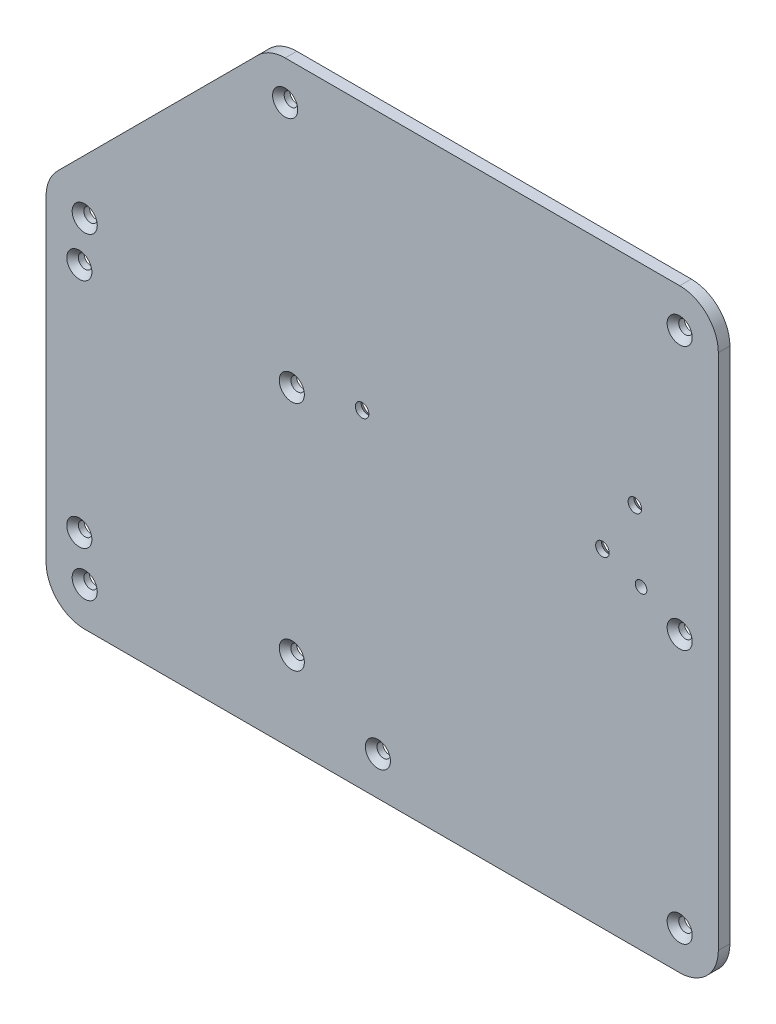
SolidWorks part; units mm, degrees
ref_plane "Piano frontale" through (0, 0, 0) normal (0, 0, 1) x (1, 0, 0)
ref_plane "Piano superiore" through (0, 0, 0) normal (0, 1, 0) x (1, 0, 0)
ref_plane "Piano destro" through (0, 0, 0) normal (1, 0, 0) x (0, 0, -1)
sketch "Schizzo1" plane through (0, 0, 0) normal (0, 0, 1) x (1, 0, 0)
  line L5 (0, 0) -> (170, 0) construction
  line L6 (170, 0) -> (170, 150) construction
  line L7 (170, 150) -> (56.5685, 150) construction
  line L8 (56.5685, 150) -> (0, 93.4315) construction
  line L9 (0, 93.4315) -> (0, 0) construction
  line L10 (172, 152) -> (55.7401, 152)
  line L11 (55.7401, 152) -> (-2, 94.2599)
  line L12 (-2, 94.2599) -> (-2, -2)
  line L13 (-2, -2) -> (172, -2)
  line L14 (172, -2) -> (172, 152)
  dimension "D5" = 2
  dimension "D1" = 150
  dimension "D2" = 80
  dimension "D3" = 170
  dimension "D4" = 135
extrude "Estrusione-Estrusione1" add sketch "Schizzo1" along normal blind 3
fillet "Raccordo1" radius 10 5 edges at (172, -2, 1.5) (-2, -2, 1.5) (55.7401, 152, 1.5) (172, 152, 1.5) (-2, 94.2599, 1.5)
sketch "Schizzo2" plane through (0, 0, 3) normal (0, 0, 1) x (1, 0, 0)
  circle A0 centre (162, 142) radius 1.75
  circle A1 centre (59.8823, 142) radius 1.75
  circle A2 centre (8, 90.1177) radius 1.75
  circle A3 centre (8, 8) radius 1.75
  circle A4 centre (162, 8) radius 1.75
  circle A5 centre (162, 73.8294) radius 1.75
  circle A6 centre (83.8818, 8) radius 1.75
  point P20 (0, 0)
  point P21 (0, 0)
  dimension "D1" = 3.5
extrude "Taglio-Estrusione1" cut sketch "Schizzo2" against normal blind 3
chamfer "Smusso1" distance 1.5 angle 45 7 edges at (163.75, 8, 3) (9.75, 8, 3) (9.75, 90.1177, 3) (61.6323, 142, 3) (163.75, 142, 3) (163.75, 73.8294, 3) (85.6318, 8, 3)
sketch "Schizzo3" plane through (0, 0, 0) normal (0, 0, -1) x (-1, 0, 0)
  circle A1 centre (-61.6, 79) radius 1.75
  circle A3 centre (-6.6, 79) radius 1.75
  circle A4 centre (-6.6, 19) radius 1.75
  circle A6 centre (-61.6, 19) radius 1.75
  dimension "D1" = 3.5
sketch "Schizzo4" plane through (0, 0, 3) normal (0, 0, 1) x (1, 0, 0)
  line L0 (153.5, 81) -> (150.5, 78) construction
  line L1 (153.5, 78) -> (153.5, 94) construction
  circle A0 centre (150.4, 97) radius 1.75
  circle A1 centre (142, 83) radius 1.75
  circle A2 centre (79.8, 83) radius 1.75
  circle A3 centre (152, 79.5) radius 1.5
  dimension "D1" = 3.5
extrude "Taglio-Estrusione2" cut sketch "Schizzo4" against normal through all
extrude "Taglio-Estrusione3" cut sketch "Schizzo3" against normal blind 10
chamfer "Smusso2" distance 1.5 angle 45 7 edges at (8.35, 19, 3) (63.35, 19, 3) (63.35, 79, 3) (8.35, 79, 3) (152.15, 97, 0) (143.75, 83, 0) (81.55, 83, 0)
